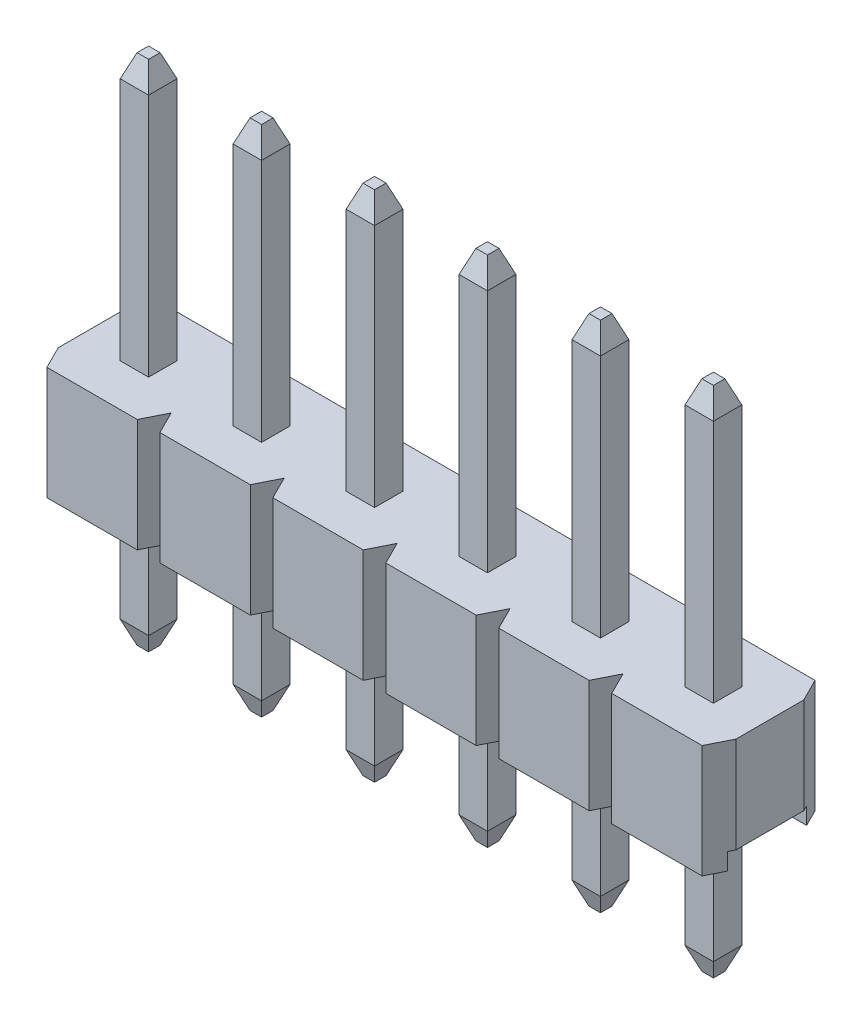
SolidWorks part; units mm, degrees
ref_plane "Front Plane" through (0, 0, 0) normal (0, 0, 1) x (1, 0, 0)
ref_plane "Top Plane" through (0, 0, 0) normal (0, 1, 0) x (1, 0, 0)
ref_plane "Right Plane" through (0, 0, 0) normal (1, 0, 0) x (0, 0, -1)
sketch "Sketch1" plane through (0, 0, 0) normal (0, 1, 0) x (1, 0, 0)
  line L1 (0, 0) -> (2.54, 0)
  line L2 (0, 0) -> (0, 2.54)
  line L3 (0, 2.54) -> (2.54, 2.54)
  line L4 (2.54, 0) -> (2.54, 2.54)
  dimension "D1" = 2.54
  dimension "D2" = 2.54
extrude "Main Body" add sketch "Sketch1" along normal blind 2.54
sketch "Sketch3" plane through (0, 0, 0) normal (-1, 0, 0) x (0, 0, 1)
  line L0 (-2.54, 0) -> (0, 0) construction
  line L1 (-2.159, 0) -> (-0.381, 0)
  line L2 (-2.159, 0) -> (-2.159, 0.381)
  line L3 (-2.159, 0.381) -> (-0.381, 0.381)
  line L4 (-0.381, 0) -> (-0.381, 0.381)
  line L5 (-2.54, 0) -> (-2.159, 0) construction
  line L6 (-0.381, 0) -> (0, 0) construction
  dimension "D1" = 0.381
extrude "Cut-Extrude1" cut sketch "Sketch3" against normal through all
sketch "Sketch4" plane through (0, 2.54, 0) normal (0, 1, 0) x (1, 0, 0)
  line L0 (0, 2.54) -> (0, 2.032)
  line L1 (0, 2.54) -> (0, 0) construction
  line L2 (0, 2.032) -> (0.254, 2.54)
  line L3 (2.54, 2.54) -> (0, 2.54) construction
  line L4 (0.254, 2.54) -> (0, 2.54)
  line L5 (2.54, 2.54) -> (2.286, 2.54)
  line L6 (2.286, 2.54) -> (2.54, 2.032)
  line L7 (2.54, 0) -> (2.54, 2.54) construction
  line L8 (2.54, 2.032) -> (2.54, 2.54)
  line L9 (2.54, 0) -> (2.286, 0)
  line L10 (0, 0) -> (2.54, 0) construction
  line L11 (2.286, 0) -> (2.54, 0.508)
  line L12 (2.54, 0.508) -> (2.54, 0)
  line L14 (0, 0) -> (0, 0.508)
  line L15 (0, 0.508) -> (0.254, 0)
  line L16 (0.254, 0) -> (0, 0)
  line M1 (0, 2.54) -> (0, 0)
  line M2 (0, 0) -> (2.54, 0)
  line M3 (2.54, 0) -> (2.54, 2.54)
  line M4 (2.54, 2.54) -> (0, 2.54)
  dimension "D1" = 0.254
  dimension "D2" = 0.508
extrude "Cut-Extrude2" cut sketch "Sketch4" against normal through all contours L2 M1 M4 | L6 M4 M3 | L15 M1 M2 | L9 L11 L12
pattern_linear "Body Pattern" count 6 spacing 2.54 along (-1, 0, 0) of "Main Body", "Cut-Extrude1", "Cut-Extrude2"
sketch "Sketch2" plane through (0, 2.54, 0) normal (0, 1, 0) x (1, 0, 0)
  line L0 (1.27, 2.54) -> (1.27, 1.59) construction
  line L1 (0.95, 0.95) -> (1.59, 0.95)
  line L2 (0.95, 0.95) -> (0.95, 1.59)
  line L3 (0.95, 1.59) -> (1.59, 1.59)
  line L4 (1.59, 0.95) -> (1.59, 1.59)
  line L6 (2.286, 2.54) -> (0.254, 2.54) construction
  line L8 (1.27, 0.95) -> (1.27, 0) construction
  line L9 (0.254, 0) -> (2.286, 0) construction
  dimension "D1" = 0.64
extrude "Pin" add sketch "Sketch2" along normal blind 6 and the other way offset from surface (5.54 mm away) 3 other way up to face at (1.27, 0, -0.1905)
chamfer "Chamfer1" distance 0.508 distance2 0.1905 4 edges at (0.95, 8.54, -1.27) (1.27, 8.54, -1.59) (1.59, 8.54, -1.27) (1.27, 8.54, -0.95)
chamfer "Chamfer2" distance 0.1905 distance2 0.508 4 edges at (1.27, -3, -1.59) (1.59, -3, -1.27) (1.27, -3, -0.95) (0.95, -3, -1.27)
pattern_linear "Pin Pattern" count 6 spacing 2.54 along (-1, 0, 0) of "Pin", "Chamfer1", "Chamfer2"
